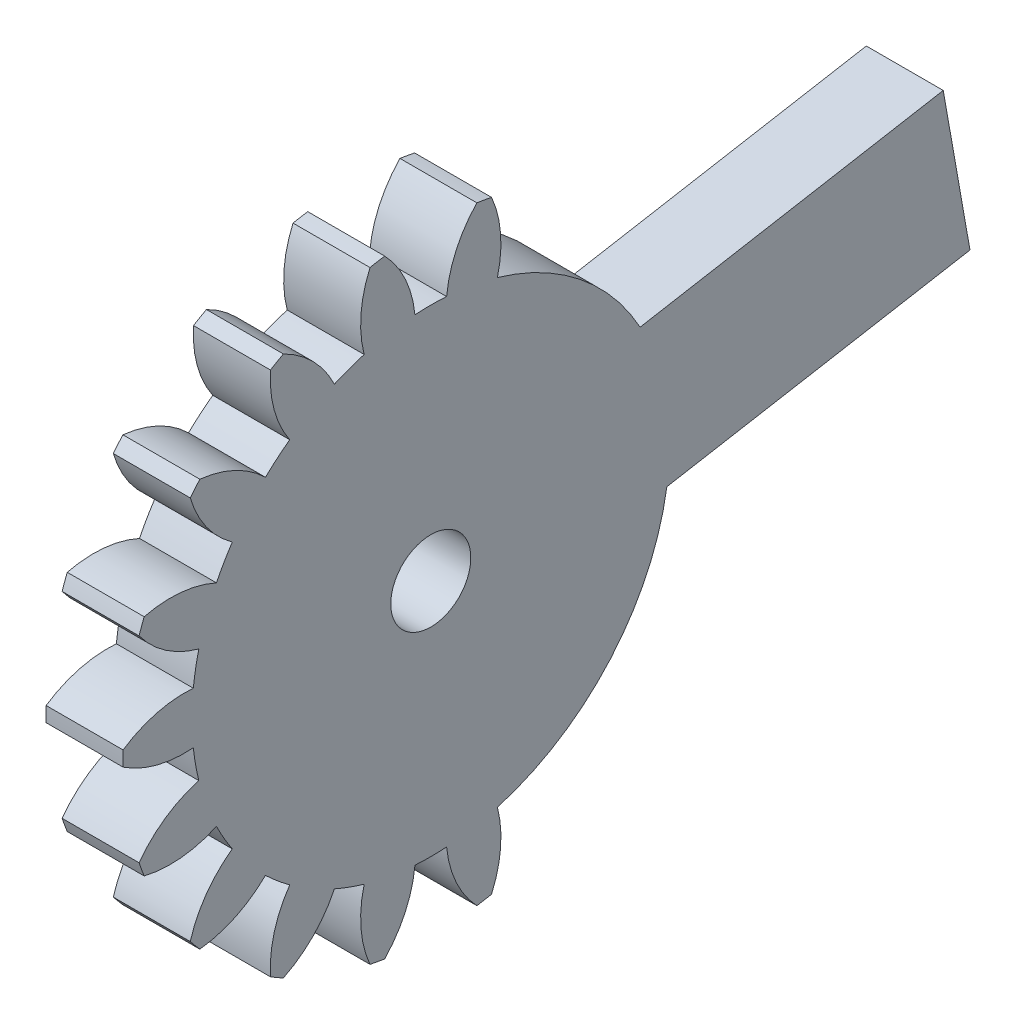
SolidWorks part; units mm, degrees
ref_plane "Plane1" through (0, 0, 0) normal (0, 0, 1) x (1, 0, 0)
ref_plane "Plane2" through (0, 0, 0) normal (0, 1, 0) x (1, 0, 0)
ref_plane "Plane3" through (0, 0, 0) normal (1, 0, 0) x (0, 0, -1)
sketch "HoldingSke" plane through (0, 0, 0) normal (0, 1, 0) x (1, 0, 0)
  line L0 (0, 0) -> (483.1367, -156.9806)
  line L1 (-15, 0) -> (100, 0) construction
  line L2 (0, 0) -> (-2.1039, 2.3779)
  line L3 (0, 0) -> (-11.863, 4.5341)
  line L4 (0, 0) -> (8.2133, 2.6687)
  line L5 (0, 0) -> (-47.5972, -17.7524)
  line L6 (0, 0) -> (-2.632, -1.7758)
  line L7 (-2.1039, 2.3779) -> (8.8308, 51.9871)
  line L8 (-76.2, 54.61) -> (-72.771, 54.61)
  line L9 (-71.009, 38.7566) -> (-53.1078, 45.2721)
  line L10 (-76.2, 71.12) -> (104.1128, 71.12)
  line L11 (0, 0) -> (-3.175, 0)
  line L12 (-76.2, 101.6) -> (-76.1492, 101.6)
  line L13 (24.9733, 27.94) -> (52.9518, 28.4284)
  line L14 (24.9733, 27.94) -> (25.0241, 27.9398)
  line L15 (24.9733, 27.94) -> (100.4021, 29.52)
  circle A0 centre (0, 0) radius 1.5875
  circle A1 centre (0, 0) radius 9.8552
  circle A2 centre (0, 0) radius 38.1
  circle A3 centre (0, 0) radius 1.5875
  dimension "MHD" = 19.7104
  dimension "Hub_dia" = 76.2
  dimension "Bore" = 3.175
  dimension "MBD" = 3.175
  dimension "Num_teeth" = 18
  dimension "Pitch_radius" = 180.3128
  dimension "Pitch" = 508
  dimension "Width" = 3.175
  dimension "Overall_len" = 50.8
  dimension "Show_teeth" = 18
  dimension "Thickness" = 3.175
  dimension "OAL" = 50.8001
  dimension "T_dim" = 3.429
  dimension "Ap" = 20
  dimension "H" = 19.05
  dimension "Backlash" = 0.0508
  dimension "Addendum_fac" = 1
  dimension "Dedendum_fac" = 1.2
  dimension "Clearance_fac" = 0.2
  dimension "Dedendum_add" = 0.0508
sketch "BasProSke" plane through (0, 0, 0) normal (0, 1, 0) x (1, 0, 0)
  line L0 (-10, 0) -> (60, 0) construction
  line L1 (0, 0) -> (0, 12.7)
  line L2 (0, 0) -> (3.175, 0)
  line L3 (3.175, 0) -> (3.175, 12.7)
  line L4 (3.175, 12.7) -> (0, 12.7)
  dimension "Diameter" = 25.4
  dimension "Thickness" = 3.175
revolve "Base-Revolve" add sketch "BasProSke" angle 360 about L0
sketch "TooCutSke" plane through (0, 0, 0) normal (1, 0, 0) x (0, 0, -1)
  line L1 (0, 0) -> (0, 107) construction
  line L2 (0, 0) -> (-1.085, 11.3784) construction
  line L3 (0, 0) -> (-3.9571, 22.4417) construction
  line L4 (-1.085, 11.3784) -> (-1.9785, 11.2208) construction
  arc A0 (0.6537, 9.8335) -> (-0.6537, 9.8335) centre (0, 0) ccw
  arc A1 (1.9234, 12.5792) -> (-1.9234, 12.5792) centre (0, 0) ccw
  circle A2 centre (0, 0) radius 11.43 construction
  circle A3 centre (0, 0) radius 10.7407 construction
  arc A4 (-0.6537, 9.8335) -> (-1.9234, 12.5792) centre (-5.2046, 9.3954) ccw
  arc A5 (1.9234, 12.5792) -> (0.6537, 9.8335) centre (5.2046, 9.3954) ccw
  dimension "Root_dia" = 19.7104
  dimension "Overcut_dia" = 25.4508
  dimension "Pitch_dia" = 22.86
  dimension "Base_dia" = 21.4814
  dimension "Flank_rad" = 4.572
  dimension "Half_ang" = 10
  dimension "Half_CT" = 0.9073
extrude "ToothCut" cut sketch "TooCutSke" along normal through all
fillet "Breaks" [suppressed] radius 0.0254
fillet "RootFillets" [suppressed] radius 0.3048
pattern_circular "TeethCuts" count 18 every 20 about axis through (-10, 0, 0) along (1, 0, 0) of "ToothCut", "RootFillets", "Breaks"
sketch "HubNeaOneSke" plane through (0, 0, 0) normal (-1, 0, 0) x (0, 0, 1)
  circle A0 centre (0, 0) radius 9.8552
  dimension "Diameter" = 19.7104
extrude "HubNearOne" [suppressed] add sketch "HubNeaOneSke" along normal blind 47.6251
sketch "HubNeaBotSke" plane through (0, 0, 0) normal (-1, 0, 0) x (0, 0, 1)
  circle A0 centre (0, 0) radius 9.8552
  dimension "Diameter" = 19.7104
extrude "HubNearBoth" [suppressed] add sketch "HubNeaBotSke" along normal blind 23.8125
ref_plane "FarPln" through (3.175, 0, 0) normal (1, 0, 0) x (0, 0, -1)
sketch "HubFarSke" plane through (3.175, 0, 0) normal (1, 0, 0) x (0, 0, -1)
  circle A0 centre (0, 0) radius 9.8552
  dimension "Diameter" = 19.7104
extrude "HubFar" [suppressed] add sketch "HubFarSke" along normal blind 23.8125
sketch "BorSke" plane through (0, 0, 0) normal (1, 0, 0) x (0, 0, -1)
  circle A0 centre (0, 0) radius 1.5875
  dimension "Diameter" = 3.175
extrude "Bore" cut sketch "BorSke" along normal mid plane 101.6001
sketch "KeySke" plane through (0, 0, 0) normal (1, 0, 0) x (0, 0, -1)
  line L0 (-0.127, 0) -> (-0.127, 1.8415)
  line L1 (-0.127, 1.8415) -> (0.127, 1.8415)
  line L2 (0.127, 1.8415) -> (0.127, 0)
  line L3 (0, 0) -> (0, 34) construction
  line L4 (-0.127, 0) -> (0.127, 0)
  dimension "Offset" = 1.8415
  dimension "Width" = 0.254
extrude "Keyway" [suppressed] cut sketch "KeySke" along normal mid plane 101.6001
pattern_circular "Keyway2" [suppressed] count 2 every 90 about axis through (-10, 0, 0) along (1, 0, 0)
sketch "Sketch3" plane through (0, 0, 0) normal (-1, 0, 0) x (0, 0, 1)
  line L0 (2.2053, 12.5071) -> (-2.2053, -12.5071) construction
  arc A0 (2.5076, 12.45) -> (1.9018, 12.5568) centre (0, 0) ccw construction
  arc A1 (-2.5076, -12.45) -> (-1.9018, -12.5568) centre (0, 0) ccw construction
sketch "Sketch7" plane through (0, 0, 0) normal (-1, 0, 0) x (0, 0, 1)
  line L0 (-8.6367, 4.7469) -> (-21.1437, 6.9522)
  line L1 (-2.8893, 9.4221) -> (-3.6524, 12.8049)
  line L3 (-3.1735, -9.3303) -> (-4.1021, -12.668)
  line L4 (-21.1437, 6.9522) -> (-22.2464, 0.6987)
  line L5 (-22.2464, 0.6987) -> (-9.7393, -1.5067)
  line L6 (2.2053, 12.5071) -> (-2.2053, -12.5071) construction
  line L8 (0.5606, -0.0988) -> (50.9626, -8.9861) construction
  circle A1 centre (0, 0) radius 9.8552 construction
  arc A2 (-3.1735, -9.3303) -> (-9.7393, -1.5067) centre (0, 0) cw
  circle A3 centre (0, 0) radius 13.3156 construction
  arc A4 (-3.6524, 12.8049) -> (-4.1021, -12.668) centre (0, 0) cw
  arc A5 (-2.8893, 9.4221) -> (-8.6367, 4.7469) centre (0, 0) ccw
  arc A6 (0.6537, 9.8335) -> (-0.6537, 9.8335) centre (0, 0) ccw construction
  circle A7 centre (0, 0) radius 1.5875 construction
  arc A8 (-2.749, 9.464) -> (-3.9775, 9.0169) centre (0, 0) ccw construction
  point P29 (-21.6951, 3.8254)
  dimension "D1" = 6.35
  dimension "D7" = 26.6313
  dimension "D2" = 12.7
  dimension "D3" = 84.453
extrude "Cut-Extrude-Thin1" cut sketch "Sketch7" against normal blind 5.08 and the other way blind 2.54 thin
sketch "Sketch8" plane through (0, 0, 0) normal (-1, 0, 0) x (0, 0, 1)
  line L0 (-21.1437, 6.9522) -> (-22.2464, 0.6987)
  line L1 (-21.1437, 6.9522) -> (-8.6367, 4.7469)
  line L2 (-22.2464, 0.6987) -> (-9.7393, -1.5067)
  line L3 (-8.6367, 4.7469) -> (-9.7393, -1.5067)
  arc A0 (-2.749, 9.464) -> (-8.8429, 4.3507) centre (0, 0) ccw construction
extrude "Boss-Extrude1" add sketch "Sketch8" against normal up to surface (3.175 mm away) up to face at (3.175, 0.2886, 2.9794)
sketch "Sketch9" plane through (0, 0, 0) normal (-1, 0, 0) x (0, 0, 1)
  circle A1 centre (0, 0) radius 1.651
  dimension "D1" = 3.302
extrude "Cut-Extrude2" cut sketch "Sketch9" against normal up to surface (3.175 mm away) up to face at (3.175, 0.2179, 3.7685)
equation "' \"Pitch@HoldingSke\" = 4"
equation "' \"Num_teeth@HoldingSke\" = 12"
equation "' \"Ap@HoldingSke\" =  20"
equation "' \"Width@HoldingSke\" = 0.5"
equation "' \"Hub_dia@HoldingSke\"= 1"
equation "' \"Overall_len@HoldingSke\" = 1.0"
equation "' \"Bore@HoldingSke\" = 0.75"
equation "' \"T_dim@HoldingSke\" = 0.85"
equation "' \"Width@KeySke\" = 0.25"
equation "' \"Show_teeth@HoldingSke\" = 13"
equation "' \"Backlash@HoldingSke\" = 0.009"
equation "' \"Addendum_fac@HoldingSke\" = 1.0"
equation "' \"Dedendum_fac@HoldingSke\" = 1.25"
equation "' \"Dedendum_add@HoldingSke\" = 0.00005"
equation "' \"Clearance_fac@HoldingSke\" = 0.25"
equation "' \"Pitch@HoldingSke\" = 0.5"
equation "' \"Num_teeth@HoldingSke\" = 23"
equation "' \"Show_teeth@HoldingSke\" = 23"
equation "' \"Backlash@HoldingSke\" = 0.0375"
equation "\"Overcut_dia@TooCutSke\" = (\"Num_teeth@HoldingSke\" + 2 * \"Addendum_fac@HoldingSke\") / \"Pitch@HoldingSke\" + 0.002"
equation "\"Pitch_dia@TooCutSke\" = \"Num_teeth@HoldingSke\" / \"Pitch@HoldingSke\""
equation "\"Base_dia@TooCutSke\" = \"Num_teeth@HoldingSke\" / \"Pitch@HoldingSke\" * cos((\"Ap@HoldingSke\"  * 3.14159265 / 180))"
equation "\"Root_dia@TooCutSke\" = (\"Num_teeth@HoldingSke\" + 2) / \"Pitch@HoldingSke\" - 2 * (\"Addendum_fac@HoldingSke\" + \"Dedendum_fac@HoldingSke\") / \"Pitch@HoldingSke\" - \"Dedendum_add@HoldingSke\" * 2"
equation "\"Half_ang@TooCutSke\" = 180 / \"Num_teeth@HoldingSke\""
equation "\"Half_CT@TooCutSke\" = \"Num_teeth@HoldingSke\" / \"Pitch@HoldingSke\" * sin((3.14159265 / 2 / \"Num_teeth@HoldingSke\")) / 2 - 7 * \"Backlash@HoldingSke\" / 4"
equation "\"Flank_rad@TooCutSke\" = \"Num_teeth@HoldingSke\" / \"Pitch@HoldingSke\" / 5"
equation "\"Radius@RootFillets\" = \"Clearance_fac@HoldingSke\" / \"Pitch@HoldingSke\" + \"Dedendum_add@HoldingSke\""
equation "\"Break_rad@Breaks\" = 0.02 / \"Pitch@HoldingSke\""
equation "\"Thickness@HoldingSke\" = \"Width@HoldingSke\""
equation "\"OAL@HoldingSke\" = \"Thickness@HoldingSke\""
equation "\"MHD@HoldingSke\" = (\"Num_teeth@HoldingSke\" + 2) / \"Pitch@HoldingSke\" - 2 * (\"Addendum_fac@HoldingSke\" + \"Dedendum_fac@HoldingSke\")  / \"Pitch@HoldingSke\" - \"Dedendum_add@HoldingSke\" * 2"
equation "\"MBD@HoldingSke\" = (\"Num_teeth@HoldingSke\" + 2) / \"Pitch@HoldingSke\" - 2 * (\"Addendum_fac@HoldingSke\" + \"Dedendum_fac@HoldingSke\")  / \"Pitch@HoldingSke\" - \"Dedendum_add@HoldingSke\" * 2 - 0.002"
equation "\"MHD@HoldingSke\" = ((sgn( \"MHD@HoldingSke\" - \"Hub_dia@HoldingSke\" )-1)*( \"MHD@HoldingSke\" - \"Hub_dia@HoldingSke\" ))/-2+ \"Hub_dia@HoldingSke\""
equation "\"MBD@HoldingSke\" = ((sgn( \"MBD@HoldingSke\" - \"Bore@HoldingSke\" )-1)*( \"MBD@HoldingSke\" - \"Bore@HoldingSke\" ))/-2+ \"Bore@HoldingSke\""
equation "\"OAL@HoldingSke\" = ((sgn( \"OAL@HoldingSke\" - \"Overall_len@HoldingSke\" )+1)*( \"OAL@HoldingSke\" - \"Overall_len@HoldingSke\" ))/2 + \"Overall_len@HoldingSke\" + 0.000002"
equation "\"Num_teeth@TeethCuts\" = int( \"Show_teeth@HoldingSke\" ) + 1"
equation "\"Num_teeth@TeethCuts\" = ((sgn( \"Num_teeth@TeethCuts\" - \"Num_teeth@HoldingSke\" )-1)*( \"Num_teeth@TeethCuts\" - \"Num_teeth@HoldingSke\" ))/-2+ \"Num_teeth@HoldingSke\""
equation "\"Num_teeth@TeethCuts\" = ((sgn( \"Num_teeth@TeethCuts\" - 2.0)+1)*( \"Num_teeth@TeethCuts\" - 2.0))/2 +2.0"
equation "\"Angle@TeethCuts\" = 360.0 / \"Num_teeth@HoldingSke\""
equation "\"Diameter@BasProSke\" = (\"Num_teeth@HoldingSke\" + 2 * \"Addendum_fac@HoldingSke\") / \"Pitch@HoldingSke\""
equation "\"Thickness@BasProSke\"  = \"Thickness@HoldingSke\""
equation "' \"Fillet_rad@BasProSke\" =  \"Thickness@HoldingSke\" * 0.05"
equation "\"MHD@HoldingSke\" = ((sgn( \"MHD@HoldingSke\" - \"Root_dia@TooCutSke\" )-1)*( \"MHD@HoldingSke\" - \"Root_dia@TooCutSke\" ))/-2+ \"Root_dia@TooCutSke\""
equation "\"Diameter@HubNeaOneSke\" = \"MHD@HoldingSke\""
equation "\"Length@HubNearOne\" = \"OAL@HoldingSke\" - \"Thickness@BasProSke\""
equation "\"Diameter@HubNeaBotSke\" = \"MHD@HoldingSke\""
equation "\"Length@HubNearBoth\" = ( \"OAL@HoldingSke\" - \"Thickness@BasProSke\" ) / 2.0"
equation "\"Thickness@FarPln\" = \"Thickness@BasProSke\""
equation "\"Diameter@HubFarSke\" = \"MHD@HoldingSke\""
equation "\"Length@HubFar\" = ( \"OAL@HoldingSke\" - \"Thickness@BasProSke\" ) / 2.0"
equation "\"Diameter@BorSke\" = \"MBD@HoldingSke\""
equation "\"D1@Bore\" = \"OAL@HoldingSke\" * 2.0"
equation "\"D1@Keyway\" = \"OAL@HoldingSke\" * 2.0"
equation "\"Offset@KeySke\" = \"T_dim@HoldingSke\" - \"MBD@HoldingSke\" / 2.0"
